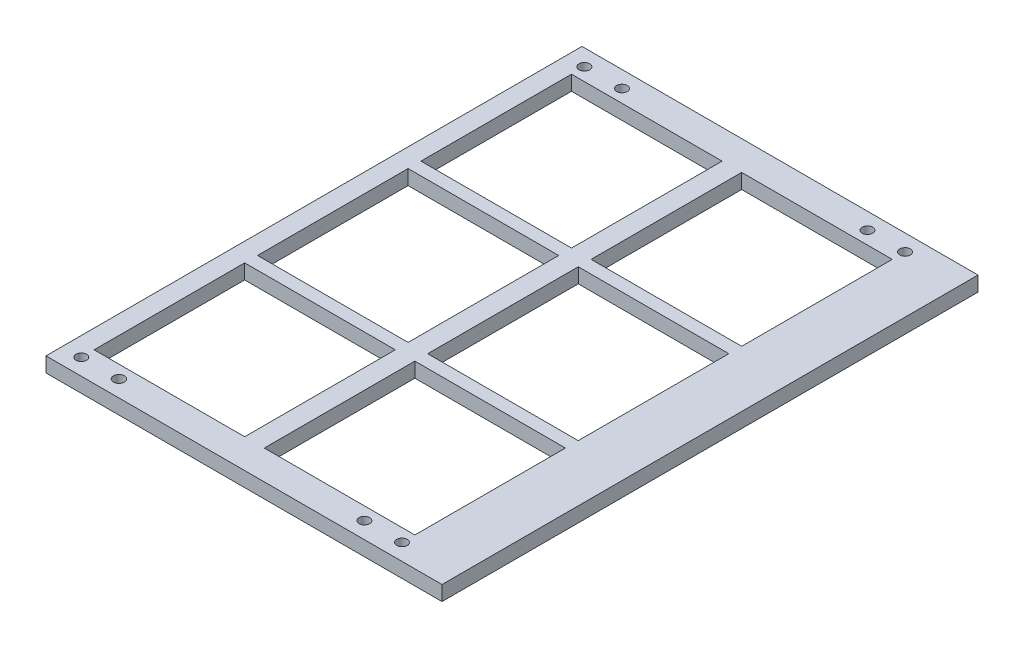
SolidWorks part; units mm, degrees
ref_plane "前视" through (0, 0, 0) normal (0, 0, 1) x (1, 0, 0)
ref_plane "上视" through (0, 0, 0) normal (0, 1, 0) x (1, 0, 0)
ref_plane "右视" through (0, 0, 0) normal (1, 0, 0) x (0, 0, -1)
sketch "Sketch1" plane through (0, 0, 0) normal (0, 1, 0) x (1, 0, 0)
  line L1 (-133.61, 180.84) -> (133.61, 180.84)
  line L2 (-133.61, 180.84) -> (-133.61, -180.84)
  line L3 (-133.61, -180.84) -> (133.61, -180.84)
  line L4 (133.61, 180.84) -> (133.61, -180.84)
  circle A0 centre (-120.91, -169.7275) radius 3.57
  circle A1 centre (-120.91, 169.7275) radius 3.57
  circle A2 centre (70.11, 169.7275) radius 3.57
  circle A3 centre (70.11, -169.7275) radius 3.57
  circle A4 centre (-95.51, 169.7275) radius 3.57
  circle A5 centre (-95.51, -169.7275) radius 3.7
  circle A6 centre (95.51, 169.7275) radius 3.57
  circle A7 centre (95.51, -169.7275) radius 3.57
  point P4 (-120.91, -169.7275)
  point P7 (70.11, -169.7275)
  point P8 (70.11, 169.7275)
  point P9 (-120.91, 169.7275)
  point P17 (-95.51, -169.7275)
  point P18 (-95.51, 169.7275)
  point P23 (95.51, -169.7275)
  point P24 (95.51, 169.7275)
  dimension "D5" = 63.5
  dimension "D7" = 191.02
  dimension "D14" = 7.14
  dimension "D16" = 25.4
  dimension "D1" = 267.22
  dimension "D2" = 361.68
  dimension "D3" = 11.1125
  dimension "D4" = 12.7
  dimension "D6" = 11.1125
  dimension "D8" = 63.5
  dimension "D9" = 11.1125
  dimension "D10" = 12.7
  dimension "D11" = 180.84
  dimension "D12" = 133.61
  dimension "D13" = 25.4
  dimension "D15" = 25.4
  dimension "D17" = 25.4
extrude "Boss-Extrude1" add sketch "Sketch1" along normal blind 10
sketch "Sketch2" plane through (0, 10, 0) normal (0, 1, 0) x (1, 0, 0)
  line L0 (-120.91, 50.8) -> (-19.31, 50.8)
  line L1 (-120.91, 50.8) -> (-120.91, -50.8)
  line L2 (-19.31, 50.8) -> (-19.31, -50.8)
  line L3 (-120.91, -50.8) -> (-19.31, -50.8)
  line L4 (-120.91, 50.8) -> (-19.31, -50.8) construction
  line L5 (-19.31, 50.8) -> (-120.91, -50.8) construction
  circle A1 centre (-120.91, 169.7275) radius 3.57 construction
  point P1 (-70.11, 0)
  dimension "D4" = 0
  dimension "D3" = 50.8
  dimension "D1" = 101.6
  dimension "D2" = 101.6
extrude "Cut-Extrude1" cut sketch "Sketch2" against normal through all
pattern_linear "LPattern1" count 2 spacing 110.265 along (0, 0, -1) of "Cut-Extrude1"
pattern_linear "LPattern2" count 2 spacing 110.265 along (0, 0, 1) of "Cut-Extrude1"
pattern_linear "LPattern3" count 2 spacing 114.82 along (1, 0, 0) of "Cut-Extrude1", "LPattern1", "LPattern2"
